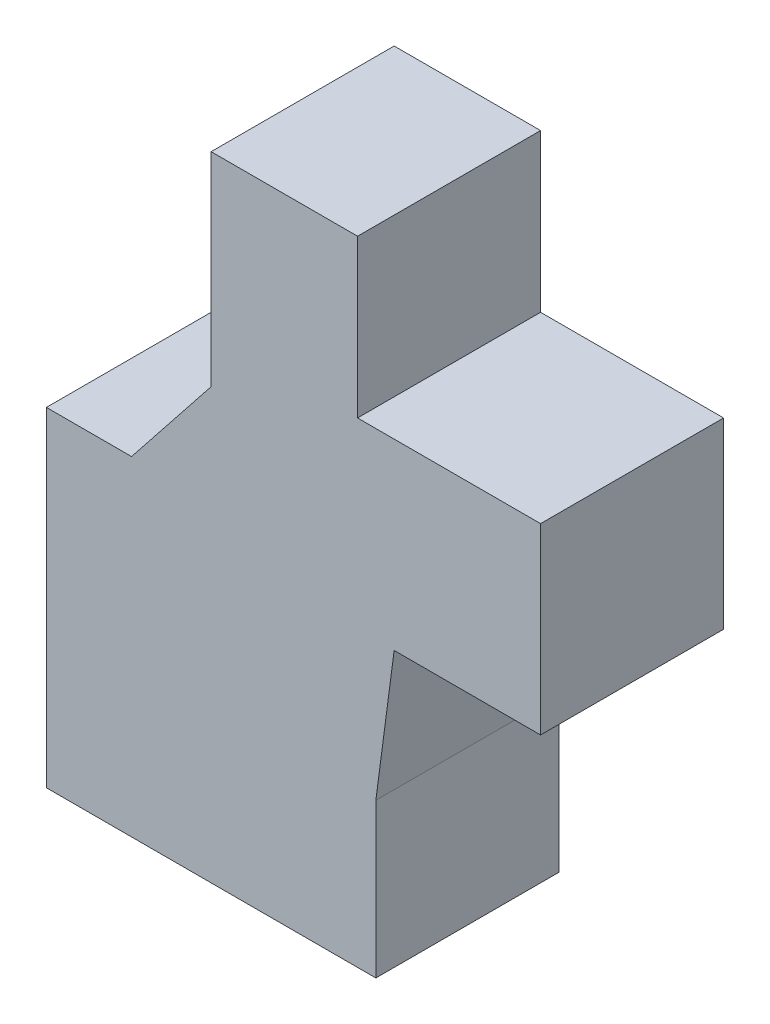
SolidWorks part; units mm, degrees
ref_plane "Front Plane" through (0, 0, 0) normal (0, 0, 1) x (1, 0, 0)
ref_plane "Top Plane" through (0, 0, 0) normal (0, 1, 0) x (1, 0, 0)
ref_plane "Right Plane" through (0, 0, 0) normal (1, 0, 0) x (0, 0, -1)
sketch "Sketch1" plane through (0, 0, 0) normal (0, 0, 1) x (1, 0, 0)
  line L0 (50, 85) -> (10, 85)
  line L1 (-45, 45) -> (45, 45)
  line L2 (-45, 45) -> (-45, -45)
  line L3 (-45, -45) -> (45, -45)
  line L4 (45, 45) -> (45, -45)
  line L5 (-45, 45) -> (45, -45) construction
  line L6 (-45, -45) -> (45, 45) construction
  line L7 (90, 85) -> (50, 85)
  line L8 (90, 85) -> (90, 35)
  line L9 (90, 35) -> (50, 35)
  line L10 (50, 85) -> (50, 35)
  line L11 (90, 85) -> (50, 35) construction
  line L12 (90, 35) -> (50, 85) construction
  line L13 (50, 35) -> (44.6145, -5.8778)
  line L14 (10, 85) -> (-35.2511, 27.9707)
  line L15 (50, 85) -> (0, 85)
  line L16 (0, 85) -> (0, 128)
  line L17 (0, 128) -> (40, 128)
  line L18 (40, 128) -> (40, 85)
  line L19 (0, 85) -> (0, 72.3971)
  circle A1 centre (0, 0) radius 45
  point P0 (0, 0)
  point P7 (70, 60)
  point P20 (0, 72.3971)
  dimension "D1" = 90
  dimension "D2" = 90
  dimension "D3" = 60
  dimension "D4" = 70
  dimension "D5" = 50
  dimension "D6" = 40
  dimension "D7" = 40
  dimension "D8" = 10
  dimension "D9" = 43
  dimension "D10" = 40
extrude "Boss-Extrude3" add sketch "Sketch1" along normal blind 50 contours A1 | L0 L14 L1 L4 L13 L10 | L7 L10 L9 L8 | A1 L4 L1 | A1 L1 L14 | L18 L17 L16 L0 L7 | L15 L19 L14 | A1 L2 L3 | A1 L14 L1 L2
